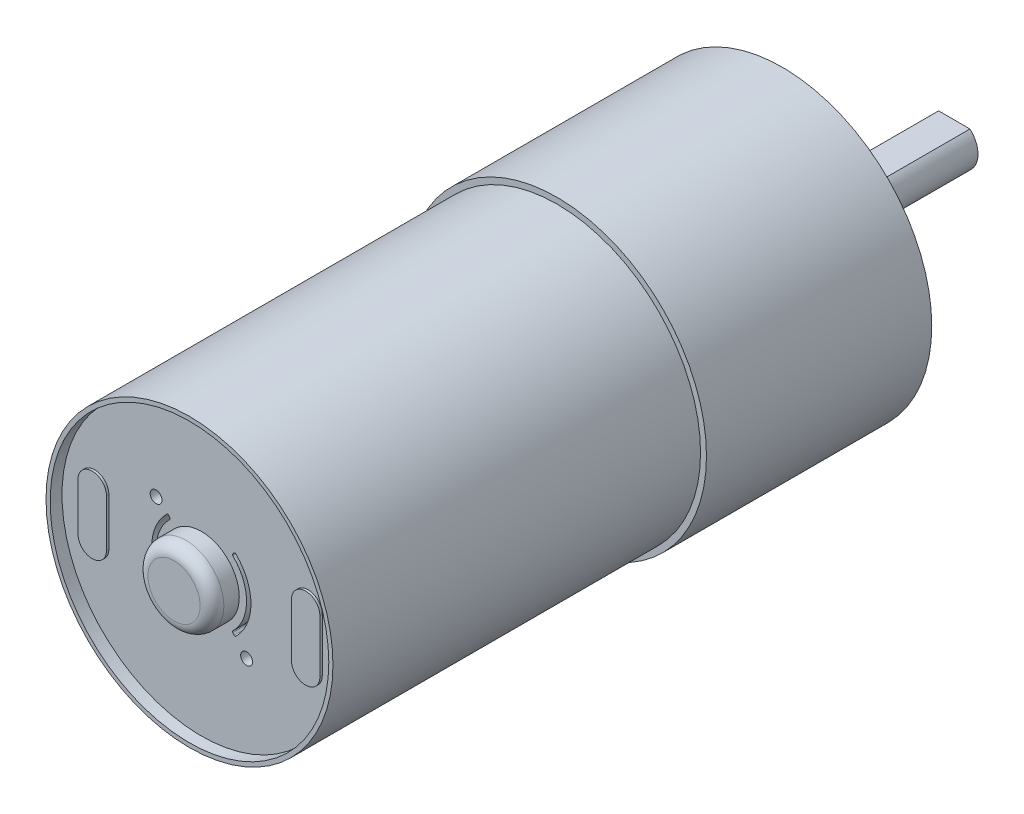
SolidWorks part; units mm, degrees
ref_plane "Front Plane" through (0, 0, 0) normal (0, 0, 1) x (1, 0, 0)
ref_plane "Top Plane" through (0, 0, 0) normal (0, 1, 0) x (1, 0, 0)
ref_plane "Right Plane" through (0, 0, 0) normal (1, 0, 0) x (0, 0, -1)
sketch "Sketch1" plane through (0, 0, 0) normal (0, 0, 1) x (1, 0, 0)
  circle A0 centre (0, 0) radius 12.6
  dimension "D1" = 25.2
extrude "Boss-Extrude1" add sketch "Sketch1" along normal blind 19
sketch "Sketch2" plane through (0, 0, 19) normal (0, 0, 1) x (1, 0, 0)
  circle A0 centre (0, 0) radius 12.1
  dimension "D1" = 24.2
extrude "Boss-Extrude2" add sketch "Sketch2" along normal blind 30
sketch "Sketch3" plane through (0, 0, 49) normal (0, 0, 1) x (1, 0, 0)
  circle A0 centre (0, 0) radius 12.1
  circle A1 centre (0, 0) radius 11.75
  dimension "D1" = 23.5
extrude "Boss-Extrude3" add sketch "Sketch3" along normal blind 1
sketch "Sketch4" plane through (0, 0, 49) normal (0, 0, 1) x (1, 0, 0)
  circle A0 centre (0, 0) radius 3.2
  dimension "D1" = 6.4
extrude "Boss-Extrude4" add sketch "Sketch4" along normal blind 2.3
fillet "Fillet1" radius 1 1 edges at (3.2, 0, 51.3)
sketch "Sketch5" plane through (0, 0, 49) normal (0, 0, 1) x (1, 0, 0)
  line L0 (-9, 2) -> (-9, -2) construction
  line L1 (-7.8, 2) -> (-7.8, -2)
  line L2 (-10.2, 2) -> (-10.2, -2)
  line L3 (9, 2.2363) -> (9, -2.2363) construction
  line L4 (10.2, 2.2363) -> (10.2, -2.2363)
  line L5 (7.8, 2.2363) -> (7.8, -2.2363)
  line L6 (-9, 0) -> (9, 0) construction
  line L7 (-9, 2) -> (9, 2.2363) construction
  arc A0 (-7.8, 2) -> (-10.2, 2) centre (-9, 2) ccw
  arc A1 (-10.2, -2) -> (-7.8, -2) centre (-9, -2) ccw
  arc A2 (10.2, 2.2363) -> (7.8, 2.2363) centre (9, 2.2363) ccw
  arc A3 (7.8, -2.2363) -> (10.2, -2.2363) centre (9, -2.2363) ccw
  point P2 (-9, 0)
  point P7 (9, 0)
  point P16 (0, 0)
  dimension "D3" = 1.2
  dimension "D4" = 1.2
  dimension "D1" = 18
  dimension "D2" = 4
extrude "Boss-Extrude5" add sketch "Sketch5" along normal blind 0.2
sketch "Sketch6" plane through (0, 0, 49) normal (0, 0, 1) x (1, 0, 0)
  line L0 (-2.7638, 3.0052) -> (-2.6496, 2.8809)
  line L1 (-2.7638, -3.0052) -> (-2.6496, -2.8809)
  line L2 (2.6496, 2.8809) -> (2.7638, 3.0052)
  line L4 (2.6496, -2.8809) -> (2.7638, -3.0052)
  arc A0 (-2.6536, 2.7414) -> (-2.6536, -2.7414) centre (0, 0) ccw
  arc A1 (-2.9069, 3.0094) -> (-2.9069, -3.0094) centre (0, 0) ccw
  circle A2 centre (-3.8153, 3.8153) radius 0.5
  circle A3 centre (3.8153, -4.1841) radius 0.5
  arc A4 (2.6536, -2.7414) -> (2.6536, 2.7414) centre (0, 0) ccw
  arc A5 (2.9069, -3.0094) -> (2.9069, 3.0094) centre (0, 0) ccw
  arc A6 (2.7638, 3.0052) -> (2.9069, 3.0094) centre (2.8374, 2.9375) cw
  arc A7 (2.6536, 2.7414) -> (2.6496, 2.8809) centre (2.7232, 2.8132) cw
  arc A8 (2.9069, -3.0094) -> (2.7638, -3.0052) centre (2.8374, -2.9375) cw
  arc A9 (2.6496, -2.8809) -> (2.6536, -2.7414) centre (2.7232, -2.8132) cw
  arc A10 (-2.6536, -2.7414) -> (-2.6496, -2.8809) centre (-2.7232, -2.8132) cw
  arc A11 (-2.7638, -3.0052) -> (-2.9069, -3.0094) centre (-2.8374, -2.9375) cw
  arc A12 (-2.6496, 2.8809) -> (-2.6536, 2.7414) centre (-2.7232, 2.8132) cw
  arc A13 (-2.7638, 3.0052) -> (-2.9069, 3.0094) centre (-2.8374, 2.9375) ccw
  point P14 (3.8153, -4.1841)
  point P15 (-3.8153, 3.8153)
  point P20 (2.5827, 2.8082)
  point P23 (2.8324, -3.0797)
  point P26 (2.5827, -2.8082)
  dimension "D1" = 0.1
extrude "Cut-Extrude1" cut sketch "Sketch6" against normal blind 20
sketch "Sketch7" plane through (0, 0, 0) normal (0, 0, -1) x (-1, 0, 0)
  line L0 (0, 0) -> (4, 10.247)
  line L1 (0, 0) -> (10.247, 4)
  line L2 (0, 0) -> (11, 0) construction
  line L3 (0, 0) -> (0, 11) construction
  circle A0 centre (0, 0) radius 11
  circle A1 centre (0, 0) radius 4.7
  dimension "D1" = 22
  dimension "D2" = 9.4
  dimension "D3" = 4
  dimension "D4" = 4
extrude "Cut-Extrude2" cut sketch "Sketch7" against normal blind 0.1 contours A1 L1 A0 L0
pattern_circular "CirPattern1" count 4 every 90 about axis through (0, 0, 0) along (0, 0, 1) of "Cut-Extrude2"
sketch "Sketch8" plane through (0, 0, 0) normal (0, 0, -1) x (-1, 0, 0)
  circle A0 centre (0, 0) radius 3.5
extrude "Boss-Extrude6" add sketch "Sketch8" along normal blind 2.5
sketch "Sketch9" plane through (0, 0, -2.5) normal (0, 0, -1) x (-1, 0, 0)
  circle A0 centre (0, 0) radius 2
extrude "Boss-Extrude7" add sketch "Sketch9" along normal blind 12
sketch "Sketch10" plane through (0, 0, -14.5) normal (0, 0, -1) x (-1, 0, 0)
  line L0 (-1.3229, 1.5) -> (1.3229, 1.5)
  line L1 (0, 1.5) -> (0, -2) construction
  circle A0 centre (0, 0) radius 2 construction
  circle A1 centre (0, 0) radius 2 construction
  arc A2 (-1.3229, 1.5) -> (1.3229, 1.5) centre (0, 0) cw
  dimension "D1" = 3.5
extrude "Cut-Extrude3" cut sketch "Sketch10" against normal blind 10
sketch "Sketch11" plane through (0, 0, 0) normal (0, 0, -1) x (-1, 0, 0)
  line L0 (-8.5, 0) -> (8.5, 0) construction
  circle A0 centre (-8.5, 0) radius 1.5
  circle A1 centre (8.5, 0) radius 1.5
  point P4 (0, 0)
  dimension "D2" = 3
  dimension "D3" = 3
  dimension "D1" = 17
extrude "Cut-Extrude4" cut sketch "Sketch11" against normal blind 10
